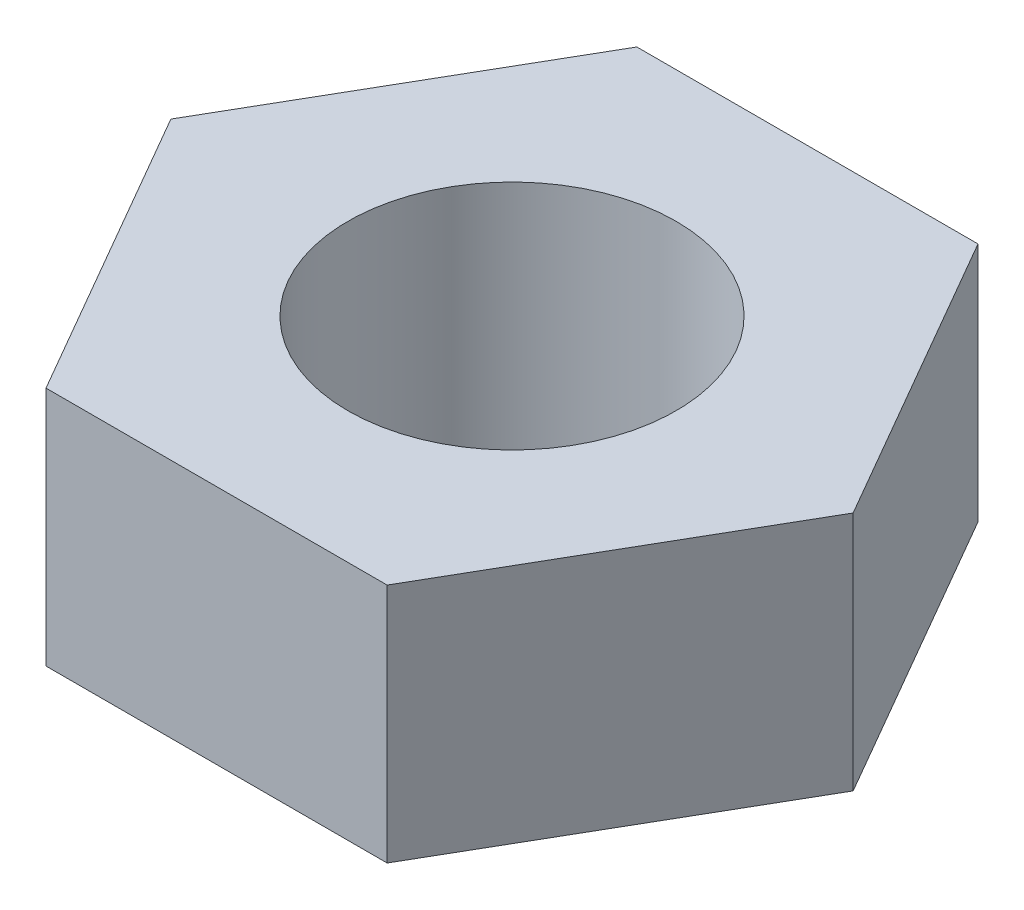
SolidWorks part; units mm, degrees
ref_plane "Alzado" through (0, 0, 0) normal (0, 0, 1) x (1, 0, 0)
ref_plane "Planta" through (0, 0, 0) normal (0, 1, 0) x (1, 0, 0)
ref_plane "Vista lateral" through (0, 0, 0) normal (1, 0, 0) x (0, 0, -1)
sketch "Croquis1" plane through (0, 0, 0) normal (0, 1, 0) x (1, 0, 0)
  line L1 (3.1177, 0) -> (1.5588, 2.7)
  line L2 (1.5588, 2.7) -> (-1.5588, 2.7)
  line L3 (-1.5588, 2.7) -> (-3.1177, 0)
  line L4 (-3.1177, 0) -> (-1.5588, -2.7)
  line L5 (-1.5588, -2.7) -> (1.5588, -2.7)
  line L6 (1.5588, -2.7) -> (3.1177, 0)
  circle A0 centre (0, 0) radius 2.7 construction
  circle A1 centre (0, 0) radius 1.5
  dimension "D2" = 3
  dimension "D1" = 5.4
extrude "Saliente-Extruir1" add sketch "Croquis1" along normal blind 2.2
